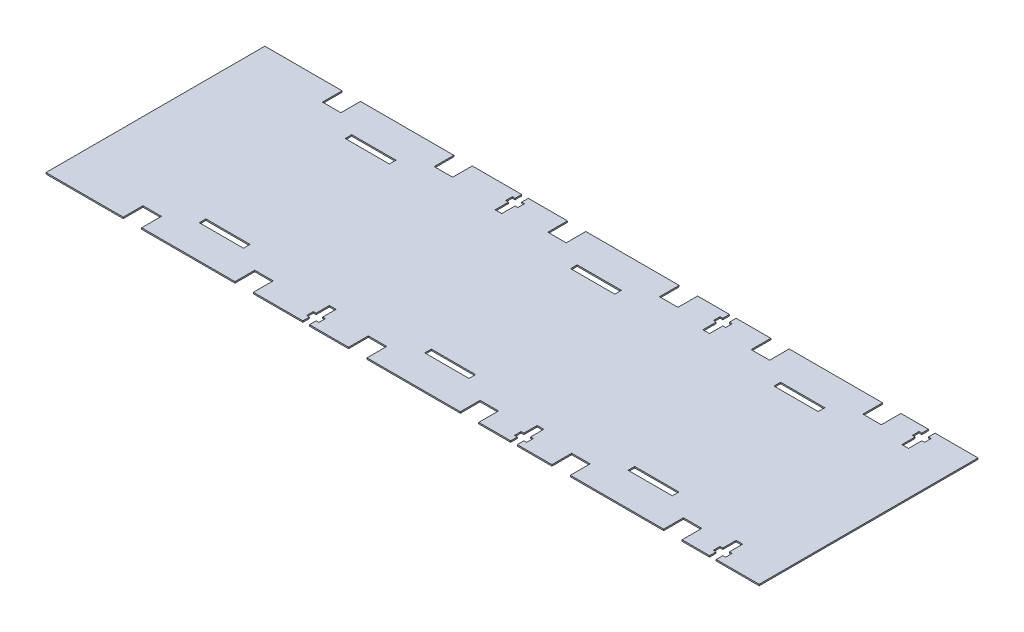
SolidWorks part; units mm, degrees
ref_plane "Front Plane" through (0, 0, 0) normal (0, 0, 1) x (1, 0, 0)
ref_plane "Top Plane" through (0, 0, 0) normal (0, 1, 0) x (1, 0, 0)
ref_plane "Right Plane" through (0, 0, 0) normal (1, 0, 0) x (0, 0, -1)
sketch "Sketch1" plane through (0, 0, 0) normal (0, 1, 0) x (1, 0, 0)
  line L0 (686.7004, 239.5797) -> (686.7004, 225.0598)
  line L1 (686.7004, 225.0598) -> (692.7497, 225.0598)
  line L2 (692.7497, 225.0598) -> (692.7497, 210.5332)
  line L3 (692.7497, 210.5332) -> (686.7004, 210.5332)
  line L4 (686.7004, 210.5332) -> (686.7004, 181.4918)
  line L5 (686.7004, 181.4918) -> (672.1788, 181.4918)
  line L6 (672.1788, 181.4918) -> (672.1788, 210.5332)
  line L7 (672.1788, 210.5332) -> (666.1294, 210.5332)
  line L8 (666.1294, 210.5332) -> (666.1294, 225.0598)
  line L9 (666.1294, 225.0598) -> (672.1788, 225.0598)
  line L10 (672.1788, 225.0598) -> (672.1788, 239.5797)
  line L11 (672.1788, 239.5797) -> (612.025, 239.5797)
  line L12 (612.025, 239.5797) -> (612.025, 196.6003)
  line L13 (612.025, 196.6003) -> (571.7235, 196.6003)
  line L14 (571.7235, 196.6003) -> (571.7235, 239.5797)
  line L15 (571.7235, 239.5797) -> (367.3464, 239.5797)
  line L16 (367.3464, 239.5797) -> (367.3464, 196.6003)
  line L17 (367.3464, 196.6003) -> (327.0432, 196.6003)
  line L18 (327.0432, 196.6003) -> (327.0432, 239.5797)
  line L19 (327.0432, 239.5797) -> (251.1007, 239.5797)
  line L20 (251.1007, 239.5797) -> (251.1007, 225.0598)
  line L21 (251.1007, 225.0598) -> (257.1501, 225.0598)
  line L22 (257.1501, 225.0598) -> (257.1501, 210.5332)
  line L23 (257.1501, 210.5332) -> (251.1007, 210.5332)
  line L24 (251.1007, 210.5332) -> (251.1007, 181.4918)
  line L25 (251.1007, 181.4918) -> (236.5791, 181.4918)
  line L26 (236.5791, 181.4918) -> (236.5791, 210.5332)
  line L27 (236.5791, 210.5332) -> (230.5297, 210.5332)
  line L28 (230.5297, 210.5332) -> (230.5297, 225.0598)
  line L29 (230.5297, 225.0598) -> (236.5791, 225.0598)
  line L30 (236.5791, 225.0598) -> (236.5791, 239.5797)
  line L31 (236.5791, 239.5797) -> (166.7477, 239.5797)
  line L32 (166.7477, 239.5797) -> (166.7477, 196.6003)
  line L33 (166.7477, 196.6003) -> (126.4462, 196.6003)
  line L34 (126.4462, 196.6003) -> (126.4462, 239.5797)
  line L35 (126.4462, 239.5797) -> (-77.9293, 239.5797)
  line L36 (-77.9293, 239.5797) -> (-77.9293, 196.6003)
  line L37 (-77.9293, 196.6003) -> (-118.2325, 196.6003)
  line L38 (-118.2325, 196.6003) -> (-118.2325, 239.5797)
  line L39 (-118.2325, 239.5797) -> (-203.8527, 239.5797)
  line L40 (-203.8527, 239.5797) -> (-203.8527, 225.0598)
  line L41 (-203.8527, 225.0598) -> (-197.8033, 225.0598)
  line L42 (-197.8033, 225.0598) -> (-197.8033, 210.5332)
  line L43 (-197.8033, 210.5332) -> (-203.8527, 210.5332)
  line L44 (-203.8527, 210.5332) -> (-203.8527, 181.4918)
  line L45 (-203.8527, 181.4918) -> (-218.3743, 181.4918)
  line L46 (-218.3743, 181.4918) -> (-218.3743, 210.5332)
  line L47 (-218.3743, 210.5332) -> (-224.4253, 210.5332)
  line L48 (-224.4253, 210.5332) -> (-224.4253, 225.0598)
  line L49 (-224.4253, 225.0598) -> (-218.3743, 225.0598)
  line L50 (-218.3743, 225.0598) -> (-218.3743, 239.5797)
  line L51 (-218.3743, 239.5797) -> (-326.6697, 239.5797)
  line L52 (-326.6697, 239.5797) -> (-326.6697, 196.6003)
  line L53 (-326.6697, 196.6003) -> (-366.9712, 196.6003)
  line L54 (-366.9712, 196.6003) -> (-366.9712, 239.5797)
  line L55 (-366.9712, 239.5797) -> (-571.3484, 239.5797)
  line L56 (-571.3484, 239.5797) -> (-571.3484, 196.6003)
  line L57 (-571.3484, 196.6003) -> (-611.6499, 196.6003)
  line L58 (-611.6499, 196.6003) -> (-611.6499, 239.5797)
  line L59 (-611.6499, 239.5797) -> (-780.7778, 239.5797)
  line L60 (-780.7778, 239.5797) -> (-780.7778, -239.5797)
  line L61 (-780.7778, -239.5797) -> (-611.6499, -239.5797)
  line L62 (-611.6499, -239.5797) -> (-611.6499, -196.3235)
  line L63 (-611.6499, -196.3235) -> (-571.3484, -196.3235)
  line L64 (-571.3484, -196.3235) -> (-571.3484, -239.5797)
  line L65 (-571.3484, -239.5797) -> (-366.9712, -239.5797)
  line L66 (-366.9712, -239.5797) -> (-366.9712, -196.3235)
  line L67 (-366.9712, -196.3235) -> (-326.6697, -196.3235)
  line L68 (-326.6697, -196.3235) -> (-326.6697, -239.5797)
  line L69 (-326.6697, -239.5797) -> (-218.3743, -239.5797)
  line L70 (-218.3743, -239.5797) -> (-218.3743, -225.0598)
  line L71 (-218.3743, -225.0598) -> (-224.4253, -225.0598)
  line L72 (-224.4253, -225.0598) -> (-224.4253, -210.5399)
  line L73 (-224.4253, -210.5399) -> (-218.3743, -210.5399)
  line L74 (-218.3743, -210.5399) -> (-218.3743, -181.5001)
  line L75 (-218.3743, -181.5001) -> (-203.8527, -181.5001)
  line L76 (-203.8527, -181.5001) -> (-203.8527, -210.5399)
  line L77 (-203.8527, -210.5399) -> (-197.8033, -210.5399)
  line L78 (-197.8033, -210.5399) -> (-197.8033, -225.0598)
  line L79 (-197.8033, -225.0598) -> (-203.8527, -225.0598)
  line L80 (-203.8527, -225.0598) -> (-203.8527, -239.5797)
  line L81 (-203.8527, -239.5797) -> (-118.2325, -239.5797)
  line L82 (-118.2325, -239.5797) -> (-118.2325, -196.3235)
  line L83 (-118.2325, -196.3235) -> (-77.9293, -196.3235)
  line L84 (-77.9293, -196.3235) -> (-77.9293, -239.5797)
  line L85 (-77.9293, -239.5797) -> (126.4462, -239.5797)
  line L86 (126.4462, -239.5797) -> (126.4462, -196.3235)
  line L87 (126.4462, -196.3235) -> (166.7477, -196.3235)
  line L88 (166.7477, -196.3235) -> (166.7477, -239.5797)
  line L89 (166.7477, -239.5797) -> (236.5825, -239.5797)
  line L90 (236.5825, -239.5797) -> (236.5825, -225.0598)
  line L91 (236.5825, -225.0598) -> (230.5331, -225.0598)
  line L92 (230.5331, -225.0598) -> (230.5331, -210.5399)
  line L93 (230.5331, -210.5399) -> (236.5825, -210.5399)
  line L94 (236.5825, -210.5399) -> (236.5825, -181.5001)
  line L95 (236.5825, -181.5001) -> (251.1023, -181.5001)
  line L96 (251.1023, -181.5001) -> (251.1023, -210.5399)
  line L97 (251.1023, -210.5399) -> (257.1517, -210.5399)
  line L98 (257.1517, -210.5399) -> (257.1517, -225.0598)
  line L99 (257.1517, -225.0598) -> (251.1023, -225.0598)
  line L100 (251.1023, -225.0598) -> (251.1023, -239.5797)
  line L101 (251.1023, -239.5797) -> (327.0466, -239.5797)
  line L102 (327.0466, -239.5797) -> (327.0466, -196.3235)
  line L103 (327.0466, -196.3235) -> (367.3497, -196.3235)
  line L104 (367.3497, -196.3235) -> (367.3497, -239.5797)
  line L105 (367.3497, -239.5797) -> (571.7169, -239.5797)
  line L106 (571.7169, -239.5797) -> (571.7169, -196.3235)
  line L107 (571.7169, -196.3235) -> (612.02, -196.3235)
  line L108 (612.02, -196.3235) -> (612.02, -239.5797)
  line L109 (612.02, -239.5797) -> (672.1721, -239.5797)
  line L110 (672.1721, -239.5797) -> (672.1721, -225.0598)
  line L111 (672.1721, -225.0598) -> (666.1211, -225.0598)
  line L112 (666.1211, -225.0598) -> (666.1211, -210.5399)
  line L113 (666.1211, -210.5399) -> (672.1721, -210.5399)
  line L114 (672.1721, -210.5399) -> (672.1721, -181.5001)
  line L115 (672.1721, -181.5001) -> (686.692, -181.5001)
  line L116 (686.692, -181.5001) -> (686.692, -210.5399)
  line L117 (686.692, -210.5399) -> (692.7414, -210.5399)
  line L118 (692.7414, -210.5399) -> (692.7414, -225.0598)
  line L119 (692.7414, -225.0598) -> (686.692, -225.0598)
  line L120 (686.692, -225.0598) -> (686.692, -239.5797)
  line L121 (686.692, -239.5797) -> (780.7778, -239.5797)
  line L122 (780.7778, -239.5797) -> (780.7778, 239.5797)
  line L123 (780.7778, 239.5797) -> (686.7004, 239.5797)
  line L124 (-421.0223, -166.9503) -> (-517.8226, -166.9503)
  line L125 (-517.8226, -166.9503) -> (-517.8226, -152.4704)
  line L126 (-517.8226, -152.4704) -> (-421.0239, -152.4704)
  line L127 (-421.0239, -152.4704) -> (-421.0223, -166.9503)
  line L128 (-421.0223, 152.4971) -> (-517.8226, 152.4971)
  line L129 (-517.8226, 152.4971) -> (-517.8226, 166.9736)
  line L130 (-517.8226, 166.9736) -> (-421.0239, 166.9736)
  line L131 (-421.0239, 166.9736) -> (-421.0223, 152.4971)
  line L132 (72.6586, -166.9503) -> (-24.1417, -166.9503)
  line L133 (-24.1417, -166.9503) -> (-24.1417, -152.4704)
  line L134 (-24.1417, -152.4704) -> (72.6586, -152.4704)
  line L135 (72.6586, -152.4704) -> (72.6586, -166.9503)
  line L136 (72.6586, 152.4971) -> (-24.1417, 152.4971)
  line L137 (-24.1417, 152.4971) -> (-24.1417, 166.9736)
  line L138 (-24.1417, 166.9736) -> (72.6586, 166.9736)
  line L139 (72.6586, 166.9736) -> (72.6586, 152.4971)
  line L140 (517.936, -166.9503) -> (421.139, -166.9503)
  line L141 (421.139, -166.9503) -> (421.139, -152.4237)
  line L142 (421.139, -152.4237) -> (517.936, -152.4237)
  line L143 (517.936, -152.4237) -> (517.936, -166.9503)
  line L144 (517.936, 152.4971) -> (421.139, 152.4971)
  line L145 (421.139, 152.4971) -> (421.139, 167.0169)
  line L146 (421.139, 167.0169) -> (517.936, 167.0169)
  line L147 (517.936, 167.0169) -> (517.936, 152.4971)
extrude "Boss-Extrude1" add sketch "Sketch1" along normal blind 3
